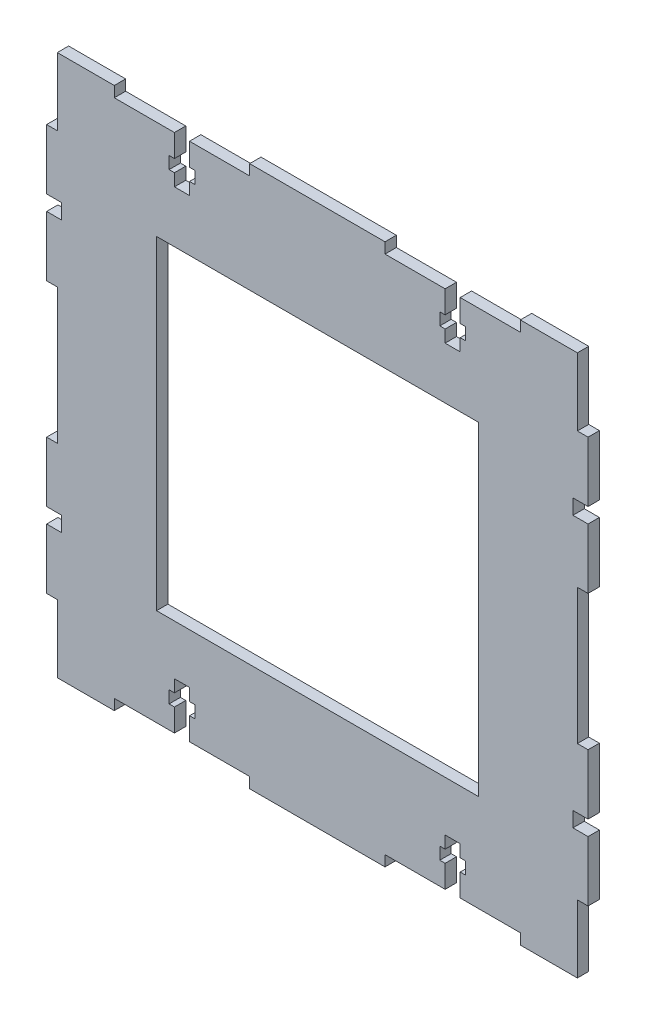
SolidWorks part; units mm, degrees
ref_plane "Front Plane" through (0, 0, 0) normal (0, 0, 1) x (1, 0, 0)
ref_plane "Top Plane" through (0, 0, 0) normal (0, 1, 0) x (1, 0, 0)
ref_plane "Right Plane" through (0, 0, 0) normal (1, 0, 0) x (0, 0, -1)
sketch "Sketch1" plane through (0, 0, 0) normal (0, 0, 1) x (1, 0, 0)
  line L0 (185.1458, 123.7471) -> (185.1458, 33.1008)
  line L1 (185.1458, 33.1008) -> (275.1189, 33.1008)
  line L2 (275.1189, 123.7471) -> (275.1189, 33.1008)
  line L3 (185.1458, 123.7471) -> (275.1189, 123.7471)
  line L132 (157.3781, 154.3975) -> (157.3781, 135.4704)
  line L133 (157.3781, 135.4704) -> (154.3975, 135.4704)
  line L134 (154.3975, 135.4704) -> (154.3975, 118.6546)
  line L135 (154.3975, 118.6546) -> (158.6201, 118.6546)
  line L136 (158.6201, 118.6546) -> (158.6201, 116.5433)
  line L137 (158.6201, 116.5433) -> (158.6201, 114.432)
  line L138 (158.6201, 114.432) -> (154.3975, 114.432)
  line L139 (154.3975, 114.432) -> (154.3975, 97.6162)
  line L140 (154.3975, 97.6162) -> (157.3781, 97.6162)
  line L141 (157.3781, 97.6162) -> (157.3781, 59.762)
  line L142 (157.3781, 59.762) -> (154.3975, 59.762)
  line L143 (154.3975, 59.762) -> (154.3975, 42.9462)
  line L144 (154.3975, 42.9462) -> (158.6201, 42.9462)
  line L145 (158.6201, 42.9462) -> (158.6201, 40.8349)
  line L146 (158.6201, 40.8349) -> (158.6201, 38.7236)
  line L147 (158.6201, 38.7236) -> (154.3975, 38.7236)
  line L148 (154.3975, 38.7236) -> (154.3975, 21.9078)
  line L149 (154.3975, 21.9078) -> (157.3781, 21.9078)
  line L150 (157.3781, 21.9078) -> (157.3781, 2.9806)
  line L151 (157.3781, 2.9806) -> (173.3246, 2.9806)
  line L152 (173.3246, 2.9806) -> (173.3246, 5.9613)
  line L153 (173.3246, 5.9613) -> (190.1404, 5.9613)
  line L154 (190.1404, 5.9613) -> (190.1404, 12.2703)
  line L155 (190.1404, 12.2703) -> (188.6501, 12.2703)
  line L156 (188.6501, 12.2703) -> (188.6501, 15.6981)
  line L157 (188.6501, 15.6981) -> (190.1404, 15.6981)
  line L158 (190.1404, 15.6981) -> (190.1404, 19.1258)
  line L159 (190.1404, 19.1258) -> (194.363, 19.1258)
  line L160 (194.363, 19.1258) -> (194.363, 15.6981)
  line L161 (194.363, 15.6981) -> (195.8533, 15.6981)
  line L162 (195.8533, 15.6981) -> (195.8533, 12.2703)
  line L163 (195.8533, 12.2703) -> (194.363, 12.2703)
  line L164 (194.363, 12.2703) -> (194.363, 5.9613)
  line L165 (194.363, 5.9613) -> (211.1788, 5.9613)
  line L166 (211.1788, 5.9613) -> (211.1788, 2.9806)
  line L167 (211.1788, 2.9806) -> (249.033, 2.9806)
  line L168 (249.033, 2.9806) -> (249.033, 5.9613)
  line L169 (249.033, 5.9613) -> (265.8489, 5.9613)
  line L170 (265.8489, 5.9613) -> (265.8489, 12.2703)
  line L171 (265.8489, 12.2703) -> (264.3585, 12.2703)
  line L172 (264.3585, 12.2703) -> (264.3585, 15.6981)
  line L173 (264.3585, 15.6981) -> (265.8489, 15.6981)
  line L174 (265.8489, 15.6981) -> (265.8489, 19.1258)
  line L175 (265.8489, 19.1258) -> (270.0714, 19.1258)
  line L176 (270.0714, 19.1258) -> (270.0714, 15.6981)
  line L177 (270.0714, 15.6981) -> (271.5618, 15.6981)
  line L178 (271.5618, 15.6981) -> (271.5618, 12.2703)
  line L179 (271.5618, 12.2703) -> (270.0714, 12.2703)
  line L180 (270.0714, 12.2703) -> (270.0714, 5.9613)
  line L181 (270.0714, 5.9613) -> (286.8873, 5.9613)
  line L182 (286.8873, 5.9613) -> (286.8873, 2.9806)
  line L183 (286.8873, 2.9806) -> (302.8337, 2.9806)
  line L184 (302.8337, 2.9806) -> (302.8337, 21.9078)
  line L185 (302.8337, 21.9078) -> (305.8144, 21.9078)
  line L186 (305.8144, 21.9078) -> (305.8144, 38.7236)
  line L187 (305.8144, 38.7236) -> (301.5918, 38.7236)
  line L188 (301.5918, 38.7236) -> (301.5918, 40.8349)
  line L189 (301.5918, 40.8349) -> (301.5918, 42.9462)
  line L190 (301.5918, 42.9462) -> (305.8144, 42.9462)
  line L191 (305.8144, 42.9462) -> (305.8144, 59.762)
  line L192 (305.8144, 59.762) -> (302.8337, 59.762)
  line L193 (302.8337, 59.762) -> (302.8337, 97.6162)
  line L194 (302.8337, 97.6162) -> (305.8144, 97.6162)
  line L195 (305.8144, 97.6162) -> (305.8144, 114.432)
  line L196 (305.8144, 114.432) -> (301.5918, 114.432)
  line L197 (301.5918, 114.432) -> (301.5918, 116.5433)
  line L198 (301.5918, 116.5433) -> (301.5918, 118.6546)
  line L199 (301.5918, 118.6546) -> (305.8144, 118.6546)
  line L200 (305.8144, 118.6546) -> (305.8144, 135.4704)
  line L201 (305.8144, 135.4704) -> (302.8337, 135.4704)
  line L202 (302.8337, 135.4704) -> (302.8337, 154.3975)
  line L203 (302.8337, 154.3975) -> (286.8873, 154.3975)
  line L204 (286.8873, 154.3975) -> (286.8873, 151.4169)
  line L205 (286.8873, 151.4169) -> (270.0714, 151.4169)
  line L206 (270.0714, 151.4169) -> (270.0714, 145.1078)
  line L207 (270.0714, 145.1078) -> (271.5618, 145.1078)
  line L208 (271.5618, 145.1078) -> (271.5618, 141.6801)
  line L209 (271.5618, 141.6801) -> (270.0714, 141.6801)
  line L210 (270.0714, 141.6801) -> (270.0714, 138.2523)
  line L211 (270.0714, 138.2523) -> (265.8489, 138.2523)
  line L212 (265.8489, 138.2523) -> (265.8489, 141.6801)
  line L213 (265.8489, 141.6801) -> (264.3585, 141.6801)
  line L214 (264.3585, 141.6801) -> (264.3585, 145.1078)
  line L215 (264.3585, 145.1078) -> (265.8489, 145.1078)
  line L216 (265.8489, 145.1078) -> (265.8489, 151.4169)
  line L217 (265.8489, 151.4169) -> (249.033, 151.4169)
  line L218 (249.033, 151.4169) -> (249.033, 154.3975)
  line L219 (249.033, 154.3975) -> (211.1788, 154.3975)
  line L220 (211.1788, 154.3975) -> (211.1788, 151.4169)
  line L221 (211.1788, 151.4169) -> (194.363, 151.4169)
  line L222 (194.363, 151.4169) -> (194.363, 145.1078)
  line L223 (194.363, 145.1078) -> (195.8533, 145.1078)
  line L224 (195.8533, 145.1078) -> (195.8533, 141.6801)
  line L225 (195.8533, 141.6801) -> (194.363, 141.6801)
  line L226 (194.363, 141.6801) -> (194.363, 138.2523)
  line L227 (194.363, 138.2523) -> (190.1404, 138.2523)
  line L228 (190.1404, 138.2523) -> (190.1404, 141.6801)
  line L229 (190.1404, 141.6801) -> (188.6501, 141.6801)
  line L230 (188.6501, 141.6801) -> (188.6501, 145.1078)
  line L231 (188.6501, 145.1078) -> (190.1404, 145.1078)
  line L232 (190.1404, 145.1078) -> (190.1404, 151.4169)
  line L233 (190.1404, 151.4169) -> (173.3246, 151.4169)
  line L234 (173.3246, 151.4169) -> (173.3246, 154.3975)
  line L235 (173.3246, 154.3975) -> (157.3781, 154.3975)
  line L629 (157.3781, 78.6891) -> (302.8337, 78.6891) construction
  line L634 (230.1059, 154.3975) -> (230.1059, 2.9806) construction
  point P0 (0, 0)
  point P684 (230.1059, 78.6891)
extrude "Boss-Extrude1" add sketch "Sketch1" along normal blind 3.175
